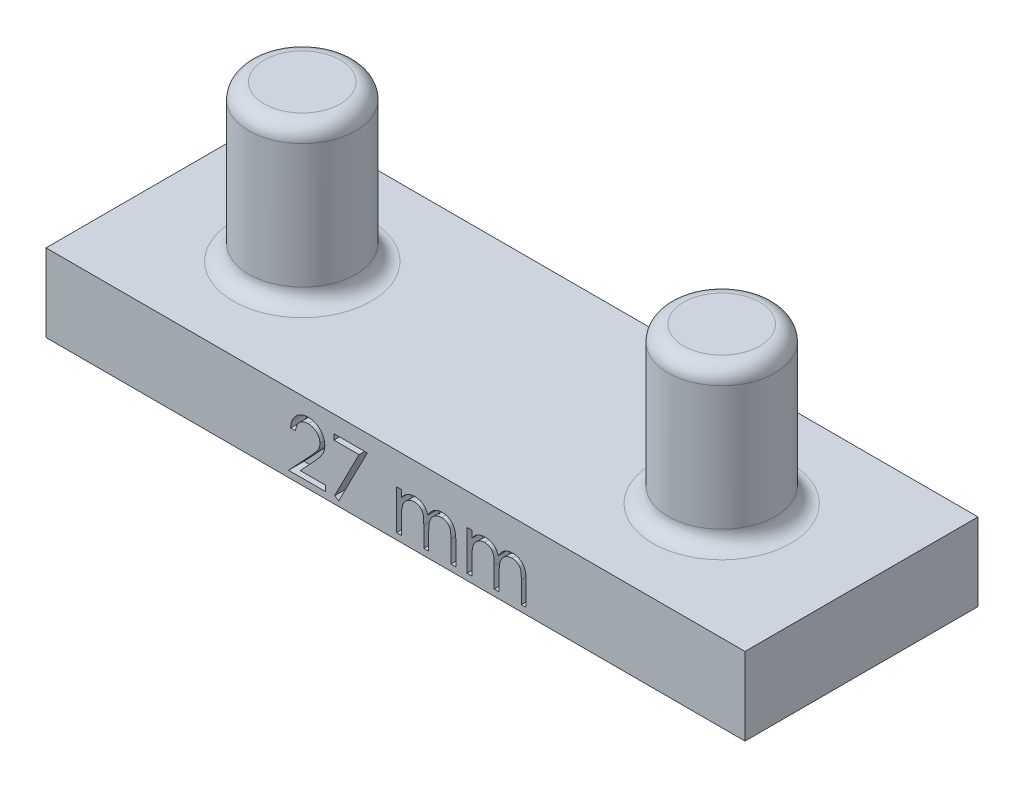
SolidWorks part; units mm, degrees
ref_plane "Front Plane" through (0, 0, 0) normal (0, 0, 1) x (1, 0, 0)
ref_plane "Top Plane" through (0, 0, 0) normal (0, 1, 0) x (1, 0, 0)
ref_plane "Right Plane" through (0, 0, 0) normal (1, 0, 0) x (0, 0, -1)
sketch "Sketch1" plane through (0, 0, 0) normal (0, 1, 0) x (1, 0, 0)
  circle A0 centre (-41.8213, 3.1021) radius 3.4487
  circle A1 centre (-14.8213, 3.1021) radius 3.4487
  dimension "D1" = 27
extrude "Boss-Extrude1" add sketch "Sketch1" along normal blind 10
sketch "Sketch2" plane through (0, 0, 0) normal (0, -1, 0) x (1, 0, 0)
  line L1 (-50.8213, 4.3979) -> (-5.8213, 4.3979)
  line L2 (-50.8213, 4.3979) -> (-50.8213, -10.6021)
  line L3 (-50.8213, -10.6021) -> (-5.8213, -10.6021)
  line L4 (-5.8213, 4.3979) -> (-5.8213, -10.6021)
  circle A0 centre (-41.8213, -3.1021) radius 3.4487 construction
  dimension "D1" = 45
  dimension "D2" = 15
  dimension "D3" = 7.5
  dimension "D4" = 9
extrude "Boss-Extrude2" add sketch "Sketch2" along normal blind 5
sketch "Sketch3" plane through (0, 0, 4.3979) normal (0, 0, 1) x (1, 0, 0)
  line L0 (-7.1347, -4.5918) -> (-47.7505, -4.5918) construction
  text T0 "27 mm"
extrude "Cut-Extrude1" cut sketch "Sketch3" against normal blind 1
fillet "Fillet1" radius 1 4 edges at (-41.8213, 0, 0.3466) (-14.8213, 0, -6.5508) (-14.8213, 10, 0.3466) (-41.8213, 10, 0.3466)
